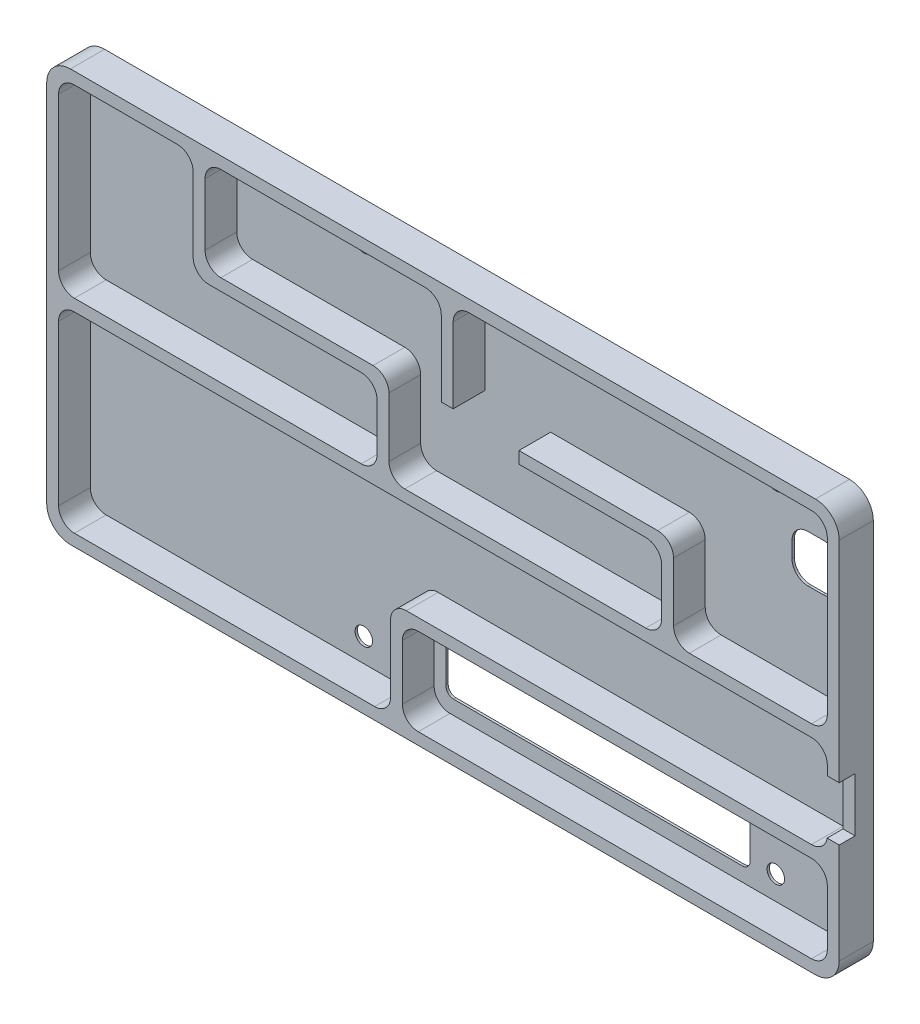
SolidWorks part; units mm, degrees
ref_plane "Front Plane" through (0, 0, 0) normal (0, 0, 1) x (1, 0, 0)
ref_plane "Top Plane" through (0, 0, 0) normal (0, 1, 0) x (1, 0, 0)
ref_plane "Right Plane" through (0, 0, 0) normal (1, 0, 0) x (0, 0, -1)
other "Configuration Table"
sketch "草图1" plane through (0, 0, 1046.4833) normal (0, 0, 1) x (1, 0, 0)
  line L0 (887.3759, 1046.1318) -> (981.3761, 1046.1318) construction
  line L1 (884.3886, 1046.1318) -> (984.3634, 1046.1318)
  line L2 (884.3886, 1046.1318) -> (884.3886, 994.1571)
  line L3 (884.3886, 994.1571) -> (984.3634, 994.1571)
  line L4 (984.3634, 1046.1318) -> (984.3634, 994.1571)
  line L6 (884.3886, 997.1444) -> (884.3886, 1043.1445) construction
  line L7 (984.3634, 1043.1445) -> (984.3634, 997.1444) construction
  line L8 (981.3761, 994.1571) -> (887.3759, 994.1571) construction
extrude "凸台-拉伸1" add sketch "草图1" along normal blind 8.6
sketch "草图2" plane through (0, 0, 1046.4833) normal (0, 0, -1) x (-1, 0, 0)
  line L0 (-884.3886, 1046.1318) -> (-884.3886, 994.1571) construction
  line L1 (-982.3634, 1044.1318) -> (-886.3886, 1044.1318)
  line L2 (-982.3634, 1044.1318) -> (-982.3634, 996.1571)
  line L3 (-982.3634, 996.1571) -> (-886.3886, 996.1571)
  line L4 (-886.3886, 1044.1318) -> (-886.3886, 996.1571)
  line L5 (-984.3634, 1046.1318) -> (-884.3886, 1046.1318) construction
  line L6 (-884.3886, 994.1571) -> (-984.3634, 994.1571) construction
  line L7 (-984.3634, 994.1571) -> (-984.3634, 1046.1318) construction
  dimension "D1" = 2
  dimension "D2" = 2
  dimension "D3" = 2
  dimension "D4" = 2
extrude "切除-拉伸1" cut sketch "草图2" against normal blind 4
sketch "草图3" plane through (0, 0, 1046.4833) normal (0, 0, -1) x (-1, 0, 0)
  line L0 (-886.3886, 996.1571) -> (-886.3886, 1044.1318) construction
  line L1 (-886.3886, 1039.1318) -> (-884.3886, 1039.1318)
  line L2 (-886.3886, 1039.1318) -> (-886.3886, 1029.1318)
  line L3 (-886.3886, 1029.1318) -> (-884.3886, 1029.1318)
  line L4 (-884.3886, 1039.1318) -> (-884.3886, 1029.1318)
  line L5 (-884.3886, 1046.1318) -> (-884.3886, 994.1571) construction
  line L8 (-984.3634, 1046.1318) -> (-884.3886, 1046.1318) construction
  line L9 (-886.3886, 1025.1318) -> (-884.3886, 1025.1318)
  line L10 (-886.3886, 1025.1318) -> (-886.3886, 1015.1571)
  line L11 (-886.3886, 1015.1571) -> (-884.3886, 1015.1571)
  line L12 (-884.3886, 1025.1318) -> (-884.3886, 1015.1571)
  line L13 (-886.3886, 1011.1571) -> (-884.3886, 1011.1571)
  line L14 (-886.3886, 1011.1571) -> (-886.3886, 1001.1571)
  line L15 (-886.3886, 1001.1571) -> (-884.3886, 1001.1571)
  line L16 (-884.3886, 1011.1571) -> (-884.3886, 1001.1571)
  line L17 (-884.3886, 994.1571) -> (-984.3634, 994.1571) construction
  dimension "D1" = 7
  dimension "D2" = 7
  dimension "D3" = 17
  dimension "D4" = 17
  dimension "D5" = 21
  dimension "D6" = 21
extrude "切除-拉伸2" cut sketch "草图3" against normal blind 3.35
sketch "草图4" plane through (0, 0, 1050.4833) normal (0, 0, -1) x (-1, 0, 0)
  line L0 (-984.3634, 1046.1318) -> (-884.3886, 1046.1318) construction
  line L1 (-969.1301, 1004.8444) -> (-930.7375, 1004.8444)
  line L2 (-969.1301, 1004.8444) -> (-969.1301, 997.4444)
  line L3 (-969.1301, 997.4444) -> (-930.7375, 997.4444)
  line L4 (-930.7375, 1004.8444) -> (-930.7375, 997.4444)
  line L5 (-980.351, 1038.1195) -> (-974.401, 1038.1195)
  line L6 (-980.351, 1038.1195) -> (-980.351, 1032.1695)
  line L7 (-980.351, 1032.1695) -> (-974.401, 1032.1695)
  line L8 (-974.401, 1038.1195) -> (-974.401, 1032.1695)
  line L9 (-984.3634, 994.1571) -> (-984.3634, 1046.1318) construction
  line L10 (-884.3886, 1046.1318) -> (-884.3886, 1039.1318) construction
  line L11 (-884.3886, 1001.1571) -> (-884.3886, 994.1571) construction
  line L12 (-884.3886, 994.1571) -> (-984.3634, 994.1571) construction
  circle A0 centre (-920.3886, 1041.6318) radius 1.1
  circle A1 centre (-920.3886, 998.6571) radius 1.1
  circle A2 centre (-972.3634, 998.6571) radius 1.1
  circle A3 centre (-972.3634, 1041.6318) radius 1.1
  dimension "D1" = 4.5
  dimension "D2" = 12
  dimension "D3" = 4.5
  dimension "D4" = 36
  dimension "D5" = 36
  dimension "D6" = 4.5
  dimension "D7" = 4.5
  dimension "D8" = 12
extrude "切除-拉伸3" cut sketch "草图4" against normal through all
sketch "草图6" plane through (0, 0, 1046.4833) normal (0, 0, -1) x (-1, 0, 0)
  line L1 (-930.3263, 1000.9528) -> (-923.5663, 1000.9528)
  line L2 (-930.3263, 1000.9528) -> (-930.3263, 994.1571)
  line L3 (-930.3263, 994.1571) -> (-923.5663, 994.1571)
  line L4 (-923.5663, 1000.9528) -> (-923.5663, 994.1571)
  line L5 (-884.3886, 994.1571) -> (-984.3634, 994.1571) construction
  line L6 (-929.8263, 995.0827) -> (-929.8263, 1000.0827) construction
  line L7 (-924.0663, 995.0827) -> (-924.0663, 1000.0827) construction
  dimension "D1" = 0.5
  dimension "D2" = 0.5
sketch "草图7" plane through (0, 0, 1055.0833) normal (0, 0, 1) x (1, 0, 0)
  line L0 (984.3634, 994.1571) -> (984.3634, 1046.1318) construction
  line L5 (984.3634, 1046.1318) -> (884.3886, 1046.1318) construction
  line L11 (885.8886, 1019.8318) -> (982.8634, 1019.8318)
  line L13 (982.8634, 1008.1318) -> (927.7634, 1008.1318)
  line L30 (934.1634, 1044.6318) -> (934.1634, 1033.1318)
  line L31 (934.1634, 1033.1318) -> (935.6634, 1033.1318)
  line L32 (935.6634, 1044.6318) -> (935.6634, 1033.1318)
  line L36 (927.7634, 1008.1318) -> (927.7634, 1006.6318)
  line L42 (927.7634, 1006.6318) -> (927.7634, 995.6571)
  line L44 (929.2634, 1006.6318) -> (929.2634, 995.6571)
  line L45 (929.2634, 1006.6318) -> (982.8634, 1006.6318)
  line L46 (961.9634, 1021.3318) -> (961.9634, 1031.2318)
  line L47 (961.9634, 1031.2318) -> (943.9634, 1031.2318)
  line L48 (943.9634, 1031.2318) -> (943.9634, 1032.7318)
  line L49 (943.9634, 1032.7318) -> (963.4634, 1032.7318)
  line L50 (963.4634, 1032.7318) -> (963.4634, 1021.3318)
  line L51 (982.8634, 1021.3318) -> (963.4634, 1021.3318)
  line L53 (926.0634, 1021.3318) -> (926.0634, 1031.3118)
  line L56 (902.8634, 1031.3118) -> (902.8634, 1044.6318)
  line L58 (904.3634, 1044.6318) -> (904.3634, 1032.8118)
  line L59 (904.3634, 1032.8118) -> (927.5634, 1032.8118)
  line L60 (927.5634, 1032.8118) -> (927.5634, 1021.3318)
  line L61 (961.9634, 1021.3318) -> (927.5634, 1021.3318)
  line L62 (926.0634, 1021.3318) -> (885.8886, 1021.3318)
  line L64 (926.0634, 1031.3118) -> (902.8634, 1031.3118)
  line L65 (982.8634, 1021.3318) -> (982.8634, 1044.6318)
  line L66 (982.8634, 1044.6318) -> (935.6634, 1044.6318)
  line L67 (904.3634, 1044.6318) -> (934.1634, 1044.6318)
  line L68 (885.8886, 1044.6318) -> (885.8886, 1021.3318)
  line L70 (902.8634, 1044.6318) -> (885.8886, 1044.6318)
  line L71 (982.8634, 1008.1318) -> (982.8634, 1019.8318)
  line L72 (885.8886, 1019.8318) -> (885.8886, 995.6571)
  line L73 (885.8886, 995.6571) -> (927.7634, 995.6571)
  line L74 (929.2634, 995.6571) -> (982.8634, 995.6571)
  line L75 (982.8634, 1006.6318) -> (982.8634, 995.6571)
  dimension "D2" = 1.5
  dimension "D3" = 20.9
  dimension "D4" = 13.4
  dimension "D5" = 1.5
  dimension "D6" = 1.5
  dimension "D7" = 38
  dimension "D8" = 56.6
  dimension "D11" = 1.5
  dimension "D12" = 19.5
  dimension "D14" = 56.8
  dimension "D15" = 26.3
  dimension "D16" = 48.7
  dimension "D17" = 13
  dimension "D18" = 1.5
  dimension "D19" = 1.5
  dimension "D20" = 1.5
  dimension "D22" = 14.82
  dimension "D23" = 1.5
  dimension "D24" = 81.5
  dimension "D25" = 1.5
fillet "圆角1" radius 3 4 edges at (984.3634, 1046.1318, 1050.7833) (884.3886, 1046.1318, 1050.7833) (884.3886, 994.1571, 1050.7833) (984.3634, 994.1571, 1050.7833)
fillet "圆角3" radius 2 4 edges at (974.401, 1038.1195, 1052.7833) (974.401, 1032.1695, 1052.7833) (980.351, 1032.1695, 1052.7833) (980.351, 1038.1195, 1052.7833)
sketch "草图12" plane through (0, 0, 1050.4833) normal (0, 0, -1) x (-1, 0, 0)
  line L1 (-959.8699, 1027.3424) -> (-950.8699, 1027.3424)
  line L2 (-959.8699, 1027.3424) -> (-959.8699, 1018.3424)
  line L3 (-959.8699, 1018.3424) -> (-950.8699, 1018.3424)
  line L4 (-950.8699, 1027.3424) -> (-950.8699, 1018.3424)
extrude "凸台-拉伸3" add sketch "草图12" along normal blind 2.7
sketch "草图13" plane through (0, 0, 1050.4833) normal (0, 0, -1) x (-1, 0, 0)
  line L1 (-944.4751, 1027.3019) -> (-927.483, 1027.3019)
  line L2 (-944.4751, 1027.3019) -> (-944.4751, 1010.2546)
  line L3 (-944.4751, 1010.2546) -> (-927.483, 1010.2546)
  line L4 (-927.483, 1027.3019) -> (-927.483, 1010.2546)
extrude "凸台-拉伸4" add sketch "草图13" along normal blind 1.9
extrude "切除-拉伸14" cut sketch "草图7" against normal blind 4
fillet "圆角7" radius 2 32 edges at (885.8886, 995.6571, 1053.0833) (982.8634, 995.6571, 1053.0833) (927.7634, 995.6571, 1053.0833) (927.7634, 1008.1318, 1053.0833) (982.8634, 1008.1318, 1053.0833) (982.8634, 1006.6318, 1053.0833) (982.8634, 1019.8318, 1053.0833) (885.8886, 1019.8318, 1053.0833) (982.8634, 1021.3318, 1053.0833) (982.8634, 1044.6318, 1053.0833) (963.4634, 1021.3318, 1053.0833) (963.4634, 1032.7318, 1053.0833) (961.9634, 1031.2318, 1053.0833) (961.9634, 1021.3318, 1053.0833) (927.5634, 1021.3318, 1053.0833) (935.6634, 1044.6318, 1053.0833) (904.3634, 1044.6318, 1053.0833) (904.3634, 1032.8118, 1053.0833) (927.5634, 1032.8118, 1053.0833) (885.8886, 1021.3318, 1053.0833) (926.0634, 1021.3318, 1053.0833) (934.1634, 1044.6318, 1053.0833) (926.0634, 1031.3118, 1053.0833) (902.8634, 1031.3118, 1053.0833) (902.8634, 1044.6318, 1053.0833) (885.8886, 1044.6318, 1053.0833) (886.3886, 996.1571, 1048.4833) (886.3886, 1044.1318, 1048.4833) (982.3634, 996.1571, 1048.4833) (982.3634, 1044.1318, 1048.4833) (929.2634, 995.6571, 1053.0833) (929.2634, 1006.6318, 1053.0833)
fillet "圆角8" radius 1 4 edges at (930.7375, 997.4444, 1050.7833) (930.7375, 1004.8444, 1050.7833) (969.1301, 997.4444, 1050.7833) (969.1301, 1004.8444, 1050.7833)
sketch "草图14" plane through (0, 0, 1055.0833) normal (0, 0, 1) x (1, 0, 0)
  line L1 (982.0396, 1016.6318) -> (984.3634, 1016.6318)
  line L2 (982.0396, 1016.6318) -> (982.0396, 1009.8318)
  line L3 (982.0396, 1009.8318) -> (984.3634, 1009.8318)
  line L4 (984.3634, 1016.6318) -> (984.3634, 1009.8318)
  line L5 (981.3634, 1046.1318) -> (887.3886, 1046.1318) construction
  line L7 (984.3634, 997.1571) -> (984.3634, 1043.1318) construction
  dimension "D1" = 29.5
  dimension "D2" = 36.3
extrude "切除-拉伸15" cut sketch "草图14" against normal blind 2
sketch "草图15" plane through (984.3634, 0, 0) normal (1, 0, 0) x (0, 0, -1)
  line L0 (-1046.4833, 994.1571) -> (-1046.4833, 997.1571) construction
  line L1 (-1050.7833, 1046.1318) -> (-1046.4833, 1046.1318)
  line L2 (-1050.7833, 1046.1318) -> (-1050.7833, 994.1571)
  line L3 (-1050.7833, 994.1571) -> (-1046.4833, 994.1571)
  line L4 (-1046.4833, 1046.1318) -> (-1046.4833, 994.1571)
  line L5 (-1055.0833, 1046.1318) -> (-1046.4833, 1046.1318) construction
  line L6 (-1046.4833, 994.1571) -> (-1055.0833, 994.1571) construction
  dimension "D1" = 4.3
extrude "切除-拉伸16" cut sketch "草图15" against normal through all
